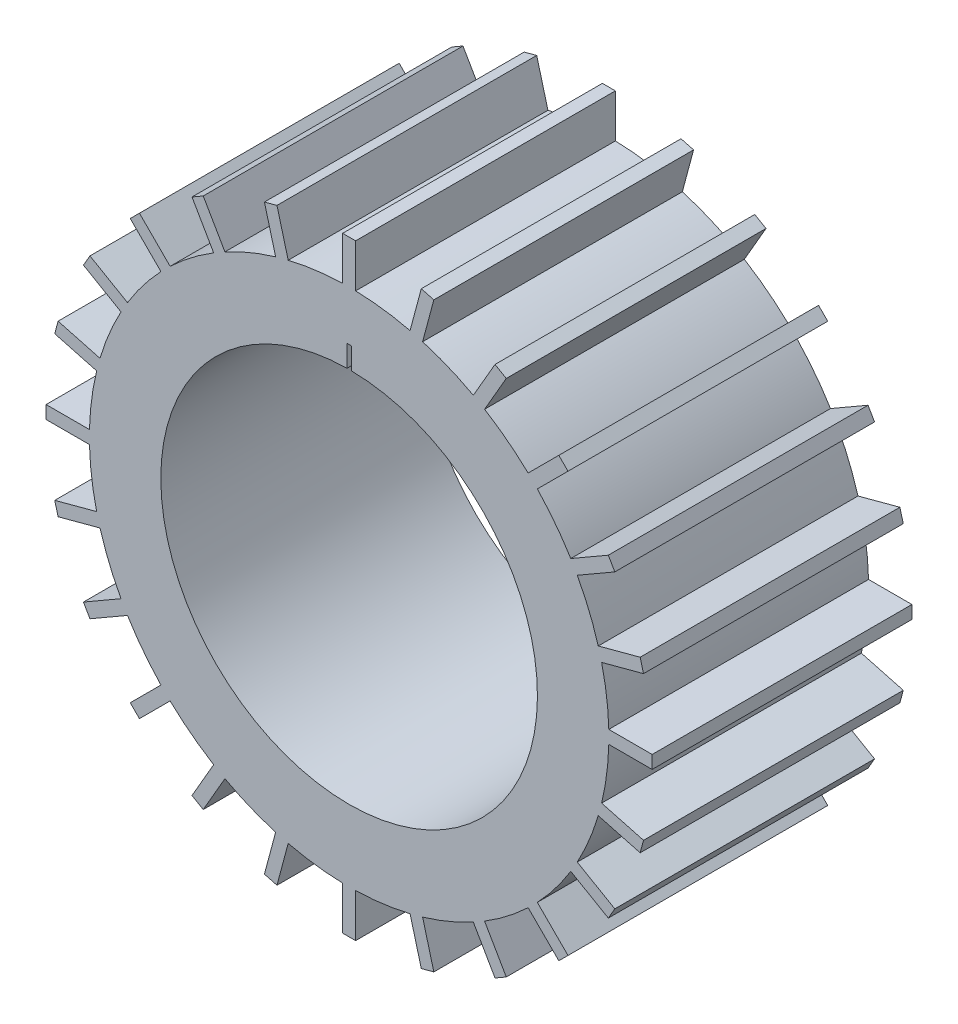
SolidWorks part; units mm, degrees
ref_plane "Front Plane" through (0, 0, 0) normal (0, 0, 1) x (1, 0, 0)
ref_plane "Top Plane" through (0, 0, 0) normal (0, 1, 0) x (1, 0, 0)
ref_plane "Right Plane" through (0, 0, 0) normal (1, 0, 0) x (0, 0, -1)
ref_plane "Plane1"
sketch "Sketch1" plane through (0, 0, 0) normal (0, 0, 1) x (1, 0, 0)
  circle A0 centre (0, 0) radius 60
  circle A1 centre (0, 0) radius 43.5
  dimension "D1" = 87
  dimension "D2" = 120
extrude "Extrusion1" add sketch "Sketch1" along normal blind 60 contours A0 A1
ref_plane "Plane2"
ref_plane "Plane3"
sketch "Sketch3" plane through (0, 0, 60) normal (0, 0, 1) x (1, 0, 0)
  line L0 (-0.5, 48.5) -> (-0.5, 43.4971)
  line L1 (0.5, 43.4971) -> (0.5, 48.5)
  line L2 (0.5, 48.5) -> (-0.5, 48.5)
  arc A0 (0.5, 43.4971) -> (-0.5, 43.4971) centre (0, 0) ccw
extrude "Extrusion3" cut sketch "Sketch3" against normal blind 60
sketch "Sketch5" plane through (0, 0, 60) normal (0, 0, 1) x (1, 0, 0)
  line L0 (14.0754, 58.3257) -> (16.6684, 68.003)
  line L1 (1.5, 59.9812) -> (1.5, 70)
  line L2 (-1.5, 59.9812) -> (-1.5, 70)
  line L3 (19.5662, 67.2266) -> (16.6684, 68.003)
  line L4 (16.9732, 57.5492) -> (19.5662, 67.2266)
  line L5 (1.5, 70) -> (-1.5, 70)
  line L6 (28.6916, 52.6953) -> (33.701, 61.3718)
  line L7 (36.299, 59.8718) -> (33.701, 61.3718)
  line L8 (31.2897, 51.1953) -> (36.299, 59.8718)
  line L9 (41.3525, 43.4738) -> (48.4368, 50.5581)
  line L10 (50.5581, 48.4368) -> (48.4368, 50.5581)
  line L11 (43.4738, 41.3525) -> (50.5581, 48.4368)
  line L12 (51.1953, 31.2897) -> (59.8718, 36.299)
  line L13 (61.3718, 33.701) -> (59.8718, 36.299)
  line L14 (52.6953, 28.6916) -> (61.3718, 33.701)
  line L15 (57.5492, 16.9732) -> (67.2266, 19.5662)
  line L16 (68.003, 16.6684) -> (67.2266, 19.5662)
  line L17 (58.3257, 14.0754) -> (68.003, 16.6684)
  line L18 (59.9812, 1.5) -> (70, 1.5)
  line L19 (70, -1.5) -> (70, 1.5)
  line L20 (59.9812, -1.5) -> (70, -1.5)
  line L21 (58.3257, -14.0754) -> (68.003, -16.6684)
  line L22 (67.2266, -19.5662) -> (68.003, -16.6684)
  line L23 (57.5492, -16.9732) -> (67.2266, -19.5662)
  line L24 (52.6953, -28.6916) -> (61.3718, -33.701)
  line L25 (59.8718, -36.299) -> (61.3718, -33.701)
  line L26 (51.1953, -31.2897) -> (59.8718, -36.299)
  line L27 (43.4738, -41.3525) -> (50.5581, -48.4368)
  line L28 (48.4368, -50.5581) -> (50.5581, -48.4368)
  line L29 (41.3525, -43.4738) -> (48.4368, -50.5581)
  line L30 (31.2897, -51.1953) -> (36.299, -59.8718)
  line L31 (33.701, -61.3718) -> (36.299, -59.8718)
  line L32 (28.6916, -52.6953) -> (33.701, -61.3718)
  line L33 (16.9732, -57.5492) -> (19.5662, -67.2266)
  line L34 (16.6684, -68.003) -> (19.5662, -67.2266)
  line L35 (14.0754, -58.3257) -> (16.6684, -68.003)
  line L36 (1.5, -59.9812) -> (1.5, -70)
  line L37 (-1.5, -70) -> (1.5, -70)
  line L38 (-1.5, -59.9812) -> (-1.5, -70)
  line L39 (-14.0754, -58.3257) -> (-16.6684, -68.003)
  line L40 (-19.5662, -67.2266) -> (-16.6684, -68.003)
  line L41 (-16.9732, -57.5492) -> (-19.5662, -67.2266)
  line L42 (-28.6916, -52.6953) -> (-33.701, -61.3718)
  line L43 (-36.299, -59.8718) -> (-33.701, -61.3718)
  line L44 (-31.2897, -51.1953) -> (-36.299, -59.8718)
  line L45 (-41.3525, -43.4738) -> (-48.4368, -50.5581)
  line L46 (-50.5581, -48.4368) -> (-48.4368, -50.5581)
  line L47 (-43.4738, -41.3525) -> (-50.5581, -48.4368)
  line L48 (-51.1953, -31.2897) -> (-59.8718, -36.299)
  line L49 (-61.3718, -33.701) -> (-59.8718, -36.299)
  line L50 (-52.6953, -28.6916) -> (-61.3718, -33.701)
  line L51 (-57.5492, -16.9732) -> (-67.2266, -19.5662)
  line L52 (-68.003, -16.6684) -> (-67.2266, -19.5662)
  line L53 (-58.3257, -14.0754) -> (-68.003, -16.6684)
  line L54 (-59.9812, -1.5) -> (-70, -1.5)
  line L55 (-70, 1.5) -> (-70, -1.5)
  line L56 (-59.9812, 1.5) -> (-70, 1.5)
  line L57 (-58.3257, 14.0754) -> (-68.003, 16.6684)
  line L58 (-67.2266, 19.5662) -> (-68.003, 16.6684)
  line L59 (-57.5492, 16.9732) -> (-67.2266, 19.5662)
  line L60 (-52.6953, 28.6916) -> (-61.3718, 33.701)
  line L61 (-59.8718, 36.299) -> (-61.3718, 33.701)
  line L62 (-51.1953, 31.2897) -> (-59.8718, 36.299)
  line L63 (-43.4738, 41.3525) -> (-50.5581, 48.4368)
  line L64 (-48.4368, 50.5581) -> (-50.5581, 48.4368)
  line L65 (-41.3525, 43.4738) -> (-48.4368, 50.5581)
  line L66 (-31.2897, 51.1953) -> (-36.299, 59.8718)
  line L67 (-33.701, 61.3718) -> (-36.299, 59.8718)
  line L68 (-28.6916, 52.6953) -> (-33.701, 61.3718)
  line L69 (-16.9732, 57.5492) -> (-19.5662, 67.2266)
  line L70 (-16.6684, 68.003) -> (-19.5662, 67.2266)
  line L71 (-14.0754, 58.3257) -> (-16.6684, 68.003)
  arc A1 (1.5, 59.9812) -> (-1.5, 59.9812) centre (0, 0) ccw
  arc A2 (16.9732, 57.5492) -> (14.0754, 58.3257) centre (0, 0) ccw
  arc A3 (31.2897, 51.1953) -> (28.6916, 52.6953) centre (0, 0) ccw
  arc A4 (43.4738, 41.3525) -> (41.3525, 43.4738) centre (0, 0) ccw
  arc A5 (52.6953, 28.6916) -> (51.1953, 31.2897) centre (0, 0) ccw
  arc A6 (58.3257, 14.0754) -> (57.5492, 16.9732) centre (0, 0) ccw
  arc A7 (59.9812, -1.5) -> (59.9812, 1.5) centre (0, 0) ccw
  arc A8 (57.5492, -16.9732) -> (58.3257, -14.0754) centre (0, 0) ccw
  arc A9 (51.1953, -31.2897) -> (52.6953, -28.6916) centre (0, 0) ccw
  arc A10 (41.3525, -43.4738) -> (43.4738, -41.3525) centre (0, 0) ccw
  arc A11 (28.6916, -52.6953) -> (31.2897, -51.1953) centre (0, 0) ccw
  arc A12 (14.0754, -58.3257) -> (16.9732, -57.5492) centre (0, 0) ccw
  arc A13 (-1.5, -59.9812) -> (1.5, -59.9812) centre (0, 0) ccw
  arc A14 (-16.9732, -57.5492) -> (-14.0754, -58.3257) centre (0, 0) ccw
  arc A15 (-31.2897, -51.1953) -> (-28.6916, -52.6953) centre (0, 0) ccw
  arc A16 (-43.4738, -41.3525) -> (-41.3525, -43.4738) centre (0, 0) ccw
  arc A17 (-52.6953, -28.6916) -> (-51.1953, -31.2897) centre (0, 0) ccw
  arc A18 (-58.3257, -14.0754) -> (-57.5492, -16.9732) centre (0, 0) ccw
  arc A19 (-59.9812, 1.5) -> (-59.9812, -1.5) centre (0, 0) ccw
  arc A20 (-57.5492, 16.9732) -> (-58.3257, 14.0754) centre (0, 0) ccw
  arc A21 (-51.1953, 31.2897) -> (-52.6953, 28.6916) centre (0, 0) ccw
  arc A22 (-41.3525, 43.4738) -> (-43.4738, 41.3525) centre (0, 0) ccw
  arc A23 (-28.6916, 52.6953) -> (-31.2897, 51.1953) centre (0, 0) ccw
  arc A24 (-14.0754, 58.3257) -> (-16.9732, 57.5492) centre (0, 0) ccw
  point P102 (0, 0)
  dimension "D1" = 24
extrude "Boss-Extrude2" add sketch "Sketch5" against normal blind 60
